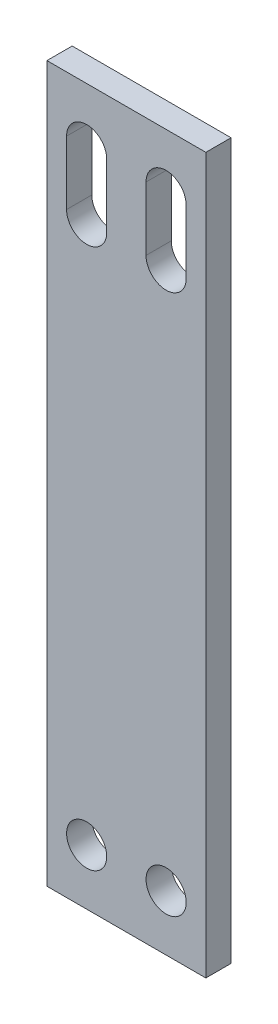
SolidWorks part; units mm, degrees
ref_plane "Front Plane" through (0, 0, 0) normal (0, 0, 1) x (1, 0, 0)
ref_plane "Top Plane" through (0, 0, 0) normal (0, 1, 0) x (1, 0, 0)
ref_plane "Right Plane" through (0, 0, 0) normal (1, 0, 0) x (0, 0, -1)
sketch "Sketch1" plane through (0, 0, 0) normal (0, 0, 1) x (1, 0, 0)
  line L0 (5, 83) -> (5, 75) construction
  line L1 (0, 0) -> (20, 0)
  line L2 (0, 0) -> (0, 90)
  line L3 (0, 90) -> (20, 90)
  line L4 (20, 0) -> (20, 90)
  line L5 (7.5273, 83) -> (7.5273, 75)
  line L6 (2.4727, 83) -> (2.4727, 75)
  line L7 (15, 75) -> (15, 83) construction
  line L8 (12.4727, 75) -> (12.4727, 83)
  line L9 (17.5273, 75) -> (17.5273, 83)
  line L10 (5, 7) -> (15, 7) construction
  line L11 (10, 7) -> (10, 0) construction
  line L12 (5, 79) -> (15, 79) construction
  line L13 (10, 79) -> (10, 7) construction
  circle A0 centre (5, 7) radius 2.5273
  circle A1 centre (15, 7) radius 2.5273
  arc A2 (7.5273, 83) -> (2.4727, 83) centre (5, 83) ccw
  arc A3 (2.4727, 75) -> (7.5273, 75) centre (5, 75) ccw
  arc A4 (12.4727, 75) -> (17.5273, 75) centre (15, 75) ccw
  arc A5 (17.5273, 83) -> (12.4727, 83) centre (15, 83) ccw
  point P11 (5, 79)
  point P16 (15, 79)
  dimension "D5" = 5.0546
  dimension "D1" = 20
  dimension "D2" = 90
  dimension "D3" = 7
  dimension "D4" = 10
  dimension "D6" = 72
  dimension "D7" = 8
extrude "Boss-Extrude1" add sketch "Sketch1" along normal blind 3.175
